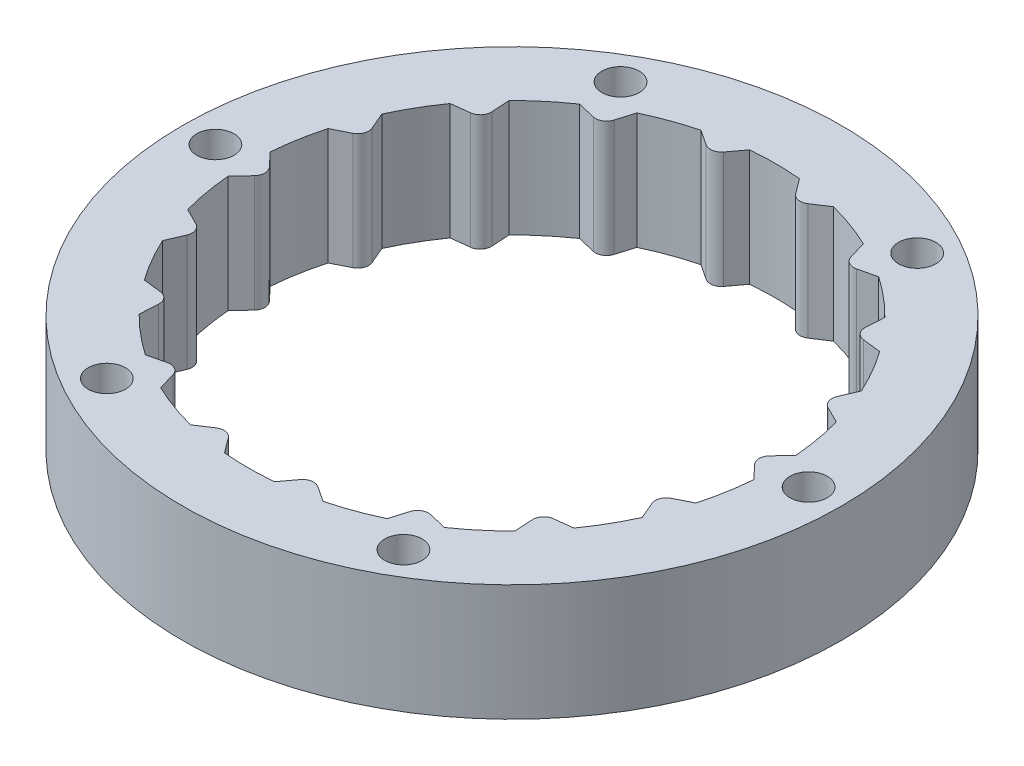
SolidWorks part; units mm, degrees
material "ABS"
ref_plane "Front Plane" through (0, 0, 0) normal (0, 0, 1) x (1, 0, 0)
ref_plane "Top Plane" through (0, 0, 0) normal (0, 1, 0) x (1, 0, 0)
ref_plane "Right Plane" through (0, 0, 0) normal (1, 0, 0) x (0, 0, -1)
sketch "Sketch1" plane through (0, 0, 0) normal (0, 0, 1) x (1, 0, 0)
  line L0 (0, 22.0264) -> (0, -14.1995) construction
  line L1 (24, 0) -> (30, 0)
  line L2 (24, 0) -> (24, 10.6)
  line L3 (24, 10.6) -> (30, 10.6)
  line L4 (30, 0) -> (30, 10.6)
  dimension "D1" = 24
  dimension "D2" = 30
  dimension "D3" = 10.6
revolve "Revolve1" add sketch "Sketch1" angle 360 about L0
sketch "Sketch4" plane through (0, 10.6, 0) normal (0, 1, 0) x (1, 0, 0)
  line L0 (22.7719, 0.6855) -> (29.0775, 7.3825)
  line L1 (22.7719, -0.6855) -> (29.0775, -7.3825)
  line L2 (0, 0) -> (23.5, 0) construction
  line L3 (0, 0) -> (22.7719, 0.6855) construction
  arc A0 (22.7719, 0.6855) -> (22.7719, -0.6855) centre (23.5, 0) ccw
  arc A1 (29.0775, 7.3825) -> (29.0775, -7.3825) centre (0, 0) cw
  circle A2 centre (0, 0) radius 30 construction
  dimension "D1" = 1
  dimension "D2" = 23.5
  dimension "D3" = 45
extrude "Boss-Extrude1" add sketch "Sketch4" against normal up to surface (10.6 mm away) up to face at (-30, 0, 0)
pattern_circular "CirPattern2" count 18 over 360 about axis through (0, 0, 0) along (0, 1, 0) of "Boss-Extrude1"
hole_wizard "M3 Clearance Hole1" positions "Sketch2" profile "Sketch3" hole size "M3" standard "ISO" end condition through all
sketch "Sketch2" plane through (0, 10.6, 0) normal (0, 1, 0) x (1, 0, 0)
  line L0 (0, 0) -> (27, 0) construction
  point P0 (27, 0)
  dimension "D1" = 27
sketch "Sketch3" plane through (27, 10.6, 0) normal (1, 0, 0) x (0, 0, 1)
  line L0 (0, 0) -> (0, 10.6)
  line L1 (0, 10.6) -> (1.7, 10.6)
  line L2 (1.7, 10.6) -> (1.7, 0)
  line L5 (1.7, 0) -> (0, 0)
  line L11 (0, -6.35) -> (0, 107.95) construction
  dimension "Thru Hole Dia." = 3.4
  dimension "Thru Hole Depth" = 10.6
pattern_circular "CirPattern1" count 6 over 360 about axis through (0, 0, 0) along (0, 1, 0) of "M3 Clearance Hole1"
equation "\"D1@Sketch1\"=24"
